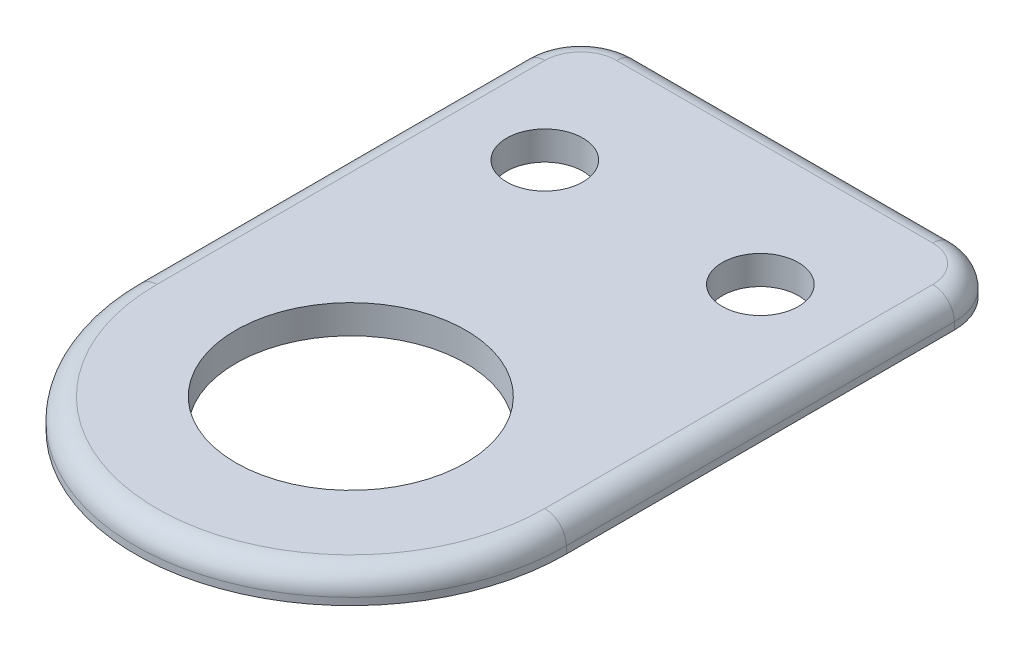
SolidWorks part; units mm, degrees
ref_plane "Front Plane" through (0, 0, 0) normal (0, 0, 1) x (1, 0, 0)
ref_plane "Top Plane" through (0, 0, 0) normal (0, 1, 0) x (1, 0, 0)
ref_plane "Right Plane" through (0, 0, 0) normal (1, 0, 0) x (0, 0, -1)
sketch "Sketch1" plane through (0, 0, 0) normal (0, 1, 0) x (1, 0, 0)
  line L0 (-15, 0) -> (15, 0)
  line L1 (-15, 0) -> (-15, 31)
  line L2 (-15, 31) -> (15, 31)
  line L3 (15, 0) -> (15, 31)
  circle A0 centre (0, 0) radius 11
  arc A1 (15, 0) -> (-15, 0) centre (0, 0) cw
  circle A2 centre (0, 0) radius 8
  point P0 (0, 0)
  point P7 (11, 0)
  point P8 (-11, 0)
  point P9 (0, 11)
  point P11 (0, 0)
  dimension "D1" = 22
  dimension "D4" = 16
  dimension "D2" = 31
  dimension "D3" = 30
extrude "Boss-Extrude1" add sketch "Sketch1" along normal blind 2 contours A0 L0 L3 L2 L1 | A2 L0 A0 | L0 A2 | L0 A2 | A2 L0 A0 | A1 L0 A0
hole_wizard "M5 Clearance Hole1" positions "3DSketch1" profile "Sketch2" hole size "M5" standard "ANSI Metric" end condition through all
sketch3d "3DSketch1"
  line L0 (-15, 2, 0) -> (-15, 2, -31) construction
  line L1 (15, 2, 0) -> (15, 2, -31) construction
  line L2 (-7.5, 2, -21) -> (7.5, 2, -21)
  line L3 (-15, 2, -31) -> (15, 2, -31) construction
  point P0 (-7.5, 2, -21)
  point P2 (7.5, 2, -21)
  dimension "D1" = 7.5
  dimension "D2" = 7.5
  dimension "D3" = 10
sketch "Sketch2" plane through (-7.5, 2, -21) normal (1, 0, 0) x (0, 0, 1)
  line L0 (0, 0) -> (0, 2)
  line L1 (0, 2) -> (2.65, 2)
  line L2 (2.65, 2) -> (2.65, 0)
  line L5 (2.65, 0) -> (0, 0)
  line L11 (0, -6.35) -> (0, 107.95) construction
  dimension "Thru Hole Dia." = 5.3
  dimension "Thru Hole Depth" = 2
fillet "Fillet1" radius 4 2 edges at (15, 1, -31) (-15, 1, -31)
fillet "Fillet2" radius 1.5 6 edges at (15, 2, -13.5) (13.8284, 2, -29.8284) (0, 2, -31) (-13.8284, 2, -29.8284) (-15, 2, -13.5) (0, 2, 15)
